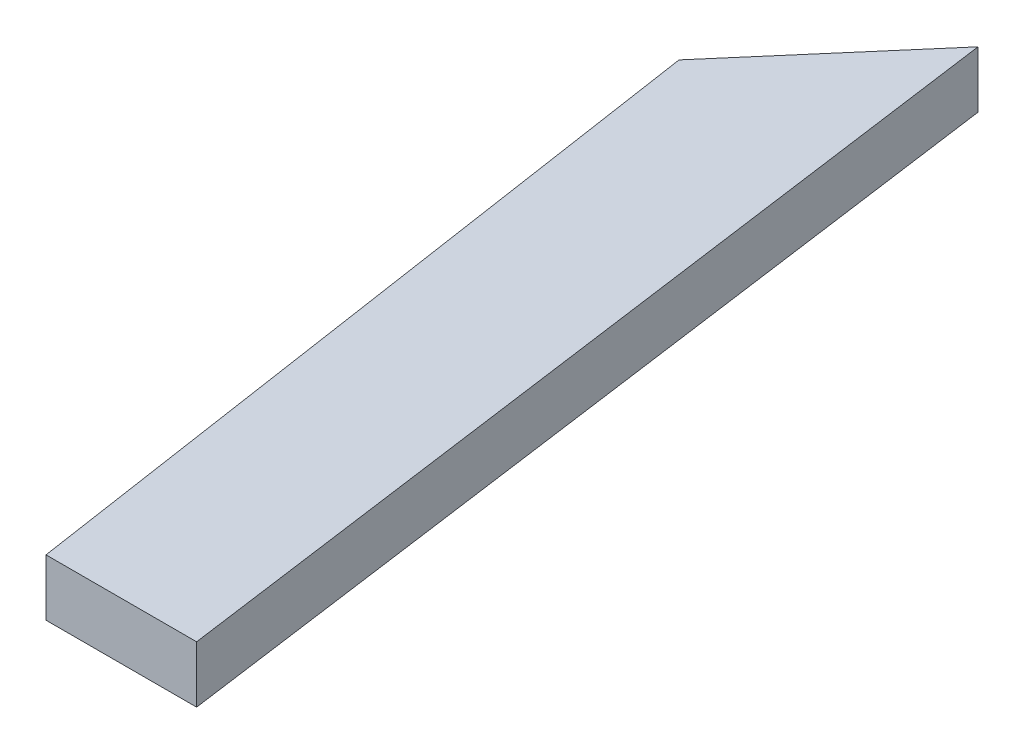
SolidWorks part; units mm, degrees
ref_plane "Front Plane" through (0, 0, 0) normal (0, 0, 1) x (1, 0, 0)
ref_plane "Top Plane" through (0, 0, 0) normal (0, 1, 0) x (1, 0, 0)
ref_plane "Right Plane" through (0, 0, 0) normal (1, 0, 0) x (0, 0, -1)
sketch "Sketch1" plane through (0, 0, 0) normal (0, 1, 0) x (1, 0, 0)
  line L0 (0, 0) -> (33.782, 0)
  line L1 (33.782, 0) -> (5.842, 203.2)
  line L2 (0, 0) -> (-25.146, 167.132)
  line L3 (-25.146, 167.132) -> (5.842, 203.2)
  dimension "D1" = 33.782
  dimension "D2" = 27.94
  dimension "D3" = 203.2
  dimension "D4" = 167.132
  dimension "D5" = 25.146
extrude "Boss-Extrude1" add sketch "Sketch1" along normal blind 12.7
